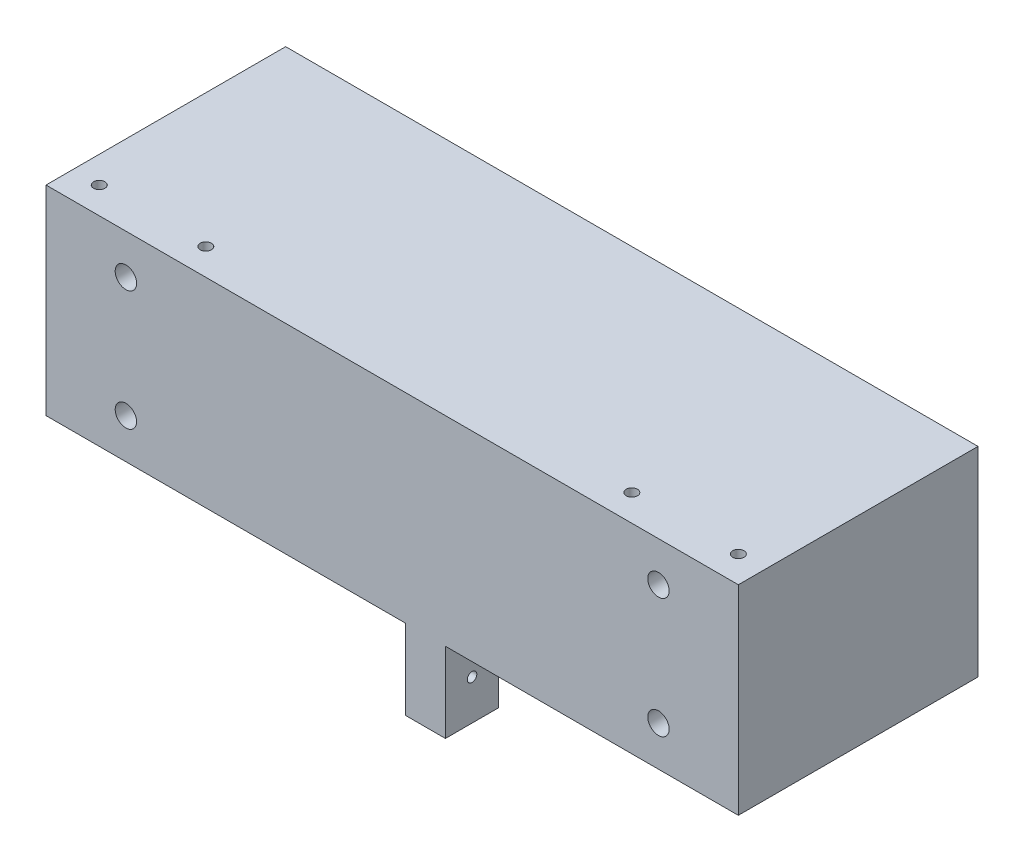
SolidWorks part; units mm, degrees
material "6061 Alloy"
ref_plane "Front Plane" through (0, 0, 0) normal (0, 0, 1) x (1, 0, 0)
ref_plane "Top Plane" through (0, 0, 0) normal (0, 1, 0) x (1, 0, 0)
ref_plane "Right Plane" through (0, 0, 0) normal (1, 0, 0) x (0, 0, -1)
sketch "Sketch1" plane through (0, 0, 0) normal (0, 1, 0) x (1, 0, 0)
  line L1 (-82.55, -28.575) -> (82.55, -28.575)
  line L2 (-82.55, -28.575) -> (-82.55, 28.575)
  line L3 (-82.55, 28.575) -> (82.55, 28.575)
  line L4 (82.55, -28.575) -> (82.55, 28.575)
  line L5 (-82.55, -28.575) -> (82.55, 28.575) construction
  line L6 (-82.55, 28.575) -> (82.55, -28.575) construction
  point P0 (0, 0)
  dimension "D1" = 57.15
  dimension "D2" = 165.1
extrude "Boss-Extrude1" add sketch "Sketch1" along normal blind 47.625 contours L1 L4 L3 L2
sketch "Sketch6" plane through (0, 0, 28.575) normal (0, 0, 1) x (1, 0, 0)
  line L0 (-82.55, 0) -> (82.55, 0) construction
  line L1 (3.175, 0) -> (12.7, 0)
  line L2 (3.175, 0) -> (3.175, -19.05)
  line L3 (3.175, -19.05) -> (12.7, -19.05)
  line L4 (12.7, 0) -> (12.7, -19.05)
  dimension "D1" = 9.525
  dimension "D2" = 12.7
  dimension "D3" = 19.05
extrude "Boss-Extrude2" add sketch "Sketch6" against normal blind 12.7 contours L3 L4 L1 L2
hole_wizard "#4-40 Tapped Hole1" positions "Sketch7" profile "Sketch8" tap size "#4-40" standard "ANSI Inch" end condition through all
sketch "Sketch7" plane through (12.7, 0, 0) normal (1, 0, 0) x (0, 0, -1)
  line L0 (-15.875, -19.05) -> (-28.575, -19.05) construction
  line L1 (-28.575, 0) -> (-28.575, -19.05) construction
  point P0 (-22.225, -9.525)
  dimension "D1" = 9.525
  dimension "D2" = 6.35
sketch "Sketch8" plane through (12.7, -9.525, 22.225) normal (0, 1, 0) x (0, 0, -1)
  line L0 (0, 0) -> (0, 95.25)
  line L1 (0, 95.25) -> (1.1303, 95.25)
  line L2 (1.1303, 95.25) -> (1.1303, 0)
  line L5 (1.1303, 0) -> (0, 0)
  line L11 (0, -6.35) -> (0, 107.95) construction
  dimension "Thru Tap Drill Dia." = 2.2606
  dimension "Thru Tap Drill Depth" = 95.25
cosmetic thread "Hole Thread1" parameters "D1"=7.112, "D2"=3.2606
hole_wizard "1/4-20 Tapped Hole1" positions "Sketch11" profile "Sketch10" tap size "1/4-20" standard "ANSI Inch" end condition through all
sketch "Sketch11" plane through (0, 0, 28.575) normal (0, 0, 1) x (1, 0, 0)
  line L0 (-82.55, 47.625) -> (-82.55, 0) construction
  line L1 (-82.55, 0) -> (3.175, 0) construction
  line L2 (-82.55, 47.625) -> (82.55, 47.625) construction
  line L3 (12.7, 0) -> (82.55, 0) construction
  line L4 (82.55, 47.625) -> (82.55, 0) construction
  point P0 (-63.5, 38.1)
  point P2 (-63.5, 9.525)
  point P4 (63.5, 38.1)
  point P6 (63.5, 9.525)
  dimension "D1" = 19.05
  dimension "D2" = 19.05
  dimension "D3" = 9.525
  dimension "D4" = 9.525
  dimension "D5" = 9.525
  dimension "D6" = 9.525
  dimension "D7" = 19.05
  dimension "D8" = 19.05
sketch "Sketch10" plane through (-63.5, 38.1, 28.575) normal (1, 0, 0) x (0, -1, 0)
  line L0 (0, 0) -> (0, 57.15)
  line L1 (0, 57.15) -> (2.5527, 57.15)
  line L2 (2.5527, 57.15) -> (2.5527, 0)
  line L5 (2.5527, 0) -> (0, 0)
  line L11 (0, -6.35) -> (0, 107.95) construction
  dimension "Thru Tap Drill Dia." = 5.1054
  dimension "Thru Tap Drill Depth" = 57.15
cosmetic thread "Hole Thread2" parameters "D2"=6.35
cosmetic thread "Hole Thread3" parameters "D2"=6.35
cosmetic thread "Hole Thread4" parameters "D2"=6.35
cosmetic thread "Hole Thread5" parameters "D2"=6.35
hole_wizard "#6-32 Tapped Hole1" positions "Sketch12" profile "Sketch13" tap size "#6-32" standard "ANSI Inch" end condition through all
sketch "Sketch12" plane through (0, 47.625, 0) normal (0, 1, 0) x (1, 0, 0)
  line L0 (-82.55, -28.575) -> (-82.55, 28.575) construction
  line L1 (-82.55, -28.575) -> (82.55, -28.575) construction
  line L2 (82.55, -28.575) -> (82.55, 28.575) construction
  point P0 (-76.2, -22.225)
  point P2 (-50.8, -22.225)
  point P4 (50.8, -22.225)
  point P6 (76.2, -22.225)
  dimension "D1" = 6.35
  dimension "D2" = 6.35
  dimension "D3" = 6.35
  dimension "D4" = 25.4
  dimension "D5" = 25.4
  dimension "D6" = 6.35
  dimension "D7" = 6.35
  dimension "D8" = 6.35
sketch "Sketch13" plane through (-76.2, 47.625, 22.225) normal (1, 0, 0) x (0, 0, 1)
  line L0 (0, 0) -> (0, 66.675)
  line L1 (0, 66.675) -> (1.3525, 66.675)
  line L2 (1.3525, 66.675) -> (1.3525, 0)
  line L5 (1.3525, 0) -> (0, 0)
  line L11 (0, -6.35) -> (0, 107.95) construction
  dimension "Thru Tap Drill Dia." = 2.7051
  dimension "Thru Tap Drill Depth" = 66.675
cosmetic thread "Hole Thread6" parameters "D2"=3.5052
cosmetic thread "Hole Thread7" parameters "D2"=3.5052
cosmetic thread "Hole Thread8" parameters "D2"=3.5052
cosmetic thread "Hole Thread9" parameters "D2"=3.5052
